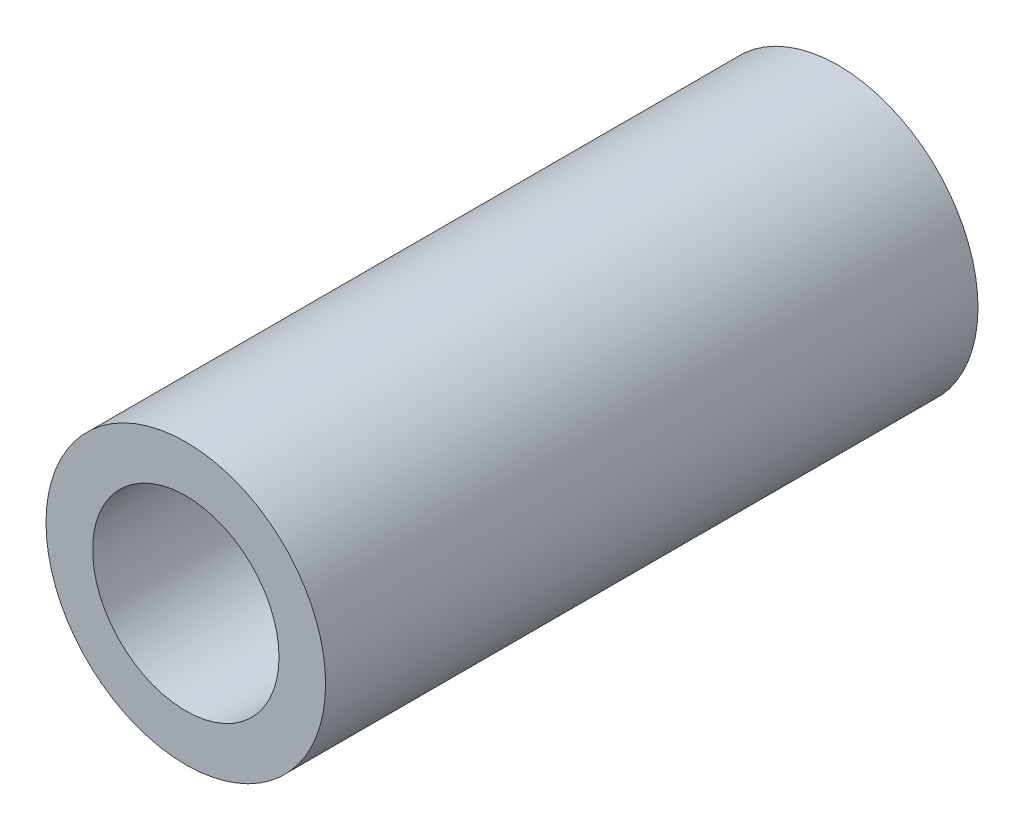
SolidWorks part; units mm, degrees
ref_plane "Front Plane" through (0, 0, 0) normal (0, 0, 1) x (1, 0, 0)
ref_plane "Top Plane" through (0, 0, 0) normal (0, 1, 0) x (1, 0, 0)
ref_plane "Right Plane" through (0, 0, 0) normal (1, 0, 0) x (0, 0, -1)
sketch "Sketch1" plane through (0, 0, 0) normal (0, 0, 1) x (1, 0, 0)
  circle A0 centre (0, 0) radius 2
  circle A1 centre (0, 0) radius 3
  dimension "D1" = 4
  dimension "D2" = 6
extrude "Boss-Extrude1" add sketch "Sketch1" along normal blind 14
